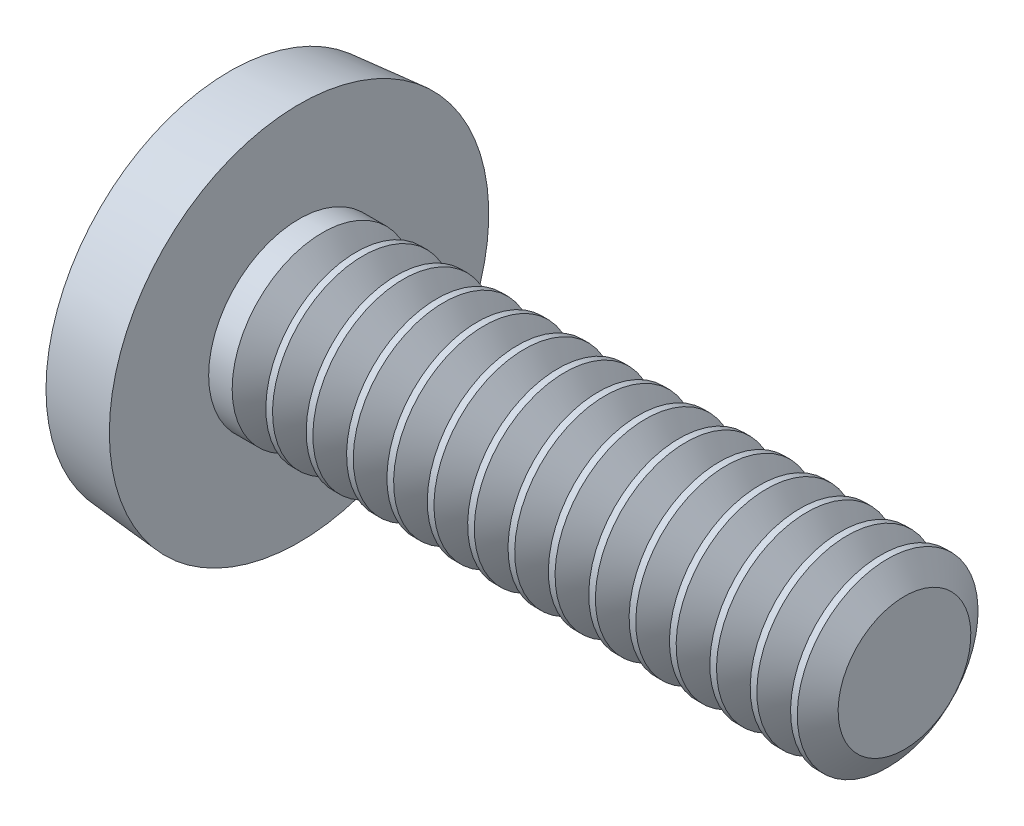
SolidWorks part; units mm, degrees
material "6061 Alloy"
ref_plane "Plane1" through (0, 0, 0) normal (0, 0, 1) x (1, 0, 0)
ref_plane "Plane2" through (0, 0, 0) normal (0, 1, 0) x (1, 0, 0)
ref_plane "Plane3" through (0, 0, 0) normal (1, 0, 0) x (0, 0, -1)
sketch "BodySke" plane through (0, 0, 0) normal (0, 0, 1) x (1, 0, 0)
  line L0 (1.7272, 1.4224) -> (1.7272, 2.9845)
  line L1 (1.7272, 2.9845) -> (0.635, 2.8889)
  line L2 (-25.4, 0) -> (127, 0) construction
  line L3 (1.7272, -2.9845) -> (0.635, -2.8889) construction
  line L4 (1.7272, 1.4224) -> (11.2522, 1.4224)
  line L5 (11.2522, 1.4224) -> (11.2522, 0)
  line L6 (11.2522, 0) -> (0, 0)
  line L7 (1.7272, -1.4224) -> (11.2522, -1.4224) construction
  line L8 (2.3622, 6.35) -> (2.3622, -3.175) construction
  line L9 (1.7272, 6.35) -> (1.7272, -3.175) construction
  arc A0 (0, 0) -> (0.635, 2.8889) centre (6.8892, 0) cw
  dimension "Head_ang" = 85
  dimension "Oval_ht" = 0.635
  dimension "Head_ht" = 1.7272
  dimension "Diameter" = 2.8448
  dimension "Length" = 9.525
  dimension "Head_dia" = 5.969
  dimension "Advance" = 0.635
  dimension "Thread_nom" = 9.525
revolve "Base-Revolve" add sketch "BodySke" angle 360 about L2
cosmetic thread "ThreadCosmetic" [suppressed] parameters "Thread_length"=8.89, "Thread_minor"=2.0879
sketch "Sketch2" plane through (0, 0, 0) normal (1, 0, 0) x (0, 0, -1)
  line L0 (2.9845, -0.4953) -> (2.9845, 0.4953)
  line L1 (2.9845, 0.4953) -> (-2.9845, 0.4953)
  line L2 (-2.9845, 0.4953) -> (-2.9845, -0.4953)
  line L3 (-2.9845, -0.4953) -> (2.9845, -0.4953)
  dimension "D1" = 5.969
  dimension "D2" = 2.9845
  dimension "D3" = 0.4953
  dimension "Slot_width" = 0.9906
extrude "Slot" [suppressed] cut sketch "Sketch2" along normal blind 1.0668
sketch "Sketch3" plane through (0, 0, 0) normal (1, 0, 0) x (0, 0, -1)
  line L0 (-0.4318, 1.9558) -> (0.4318, 1.9558)
  line L1 (0.4318, 1.9558) -> (0.4318, -1.9558)
  line L2 (0.4318, -1.9558) -> (-0.4318, -1.9558)
  line L3 (-0.4318, -1.9558) -> (-0.4318, 1.9558)
  dimension "D1" = 0.4318
  dimension "Cross_width" = 0.8636
  dimension "D2" = 1.9558
  dimension "Cross_dia" = 3.9116
ref_plane "Plane4" through (2.1844, 0, 0) normal (1, 0, 0) x (0, 0, -1)
sketch "Sketch4" plane through (2.1844, 0, 0) normal (1, 0, 0) x (0, 0, -1)
  line L0 (-0.2159, 0.2159) -> (0.2159, 0.2159)
  line L1 (0.2159, 0.2159) -> (0.2159, -0.2159)
  line L2 (0.2159, -0.2159) -> (-0.2159, -0.2159)
  line L3 (-0.2159, -0.2159) -> (-0.2159, 0.2159)
  dimension "D1" = 0.4318
  dimension "D2" = 0.2159
  dimension "D3" = 0.4318
  dimension "D4" = 0.2159
loft "Cross" cut profiles "Sketch3", "Sketch4"
pattern_circular "CirPattern1" count 2 every 90 about axis through (0, 0, 0) along (1, 0, 0) of "Cross"
sketch "ThdSchSke" plane through (0, 0, 0) normal (0, 0, 1) x (1, 0, 0)
  line L0 (2.3622, -1.0439) -> (2.0972, -1.4224)
  line L1 (2.3622, -1.0439) -> (2.6272, -1.4224)
  line L2 (2.6272, -1.4224) -> (2.6272, -1.778)
  line L3 (-3.175, 0) -> (5.1513, 0) construction
  line L5 (2.6272, -1.778) -> (2.0972, -1.778)
  line L6 (2.0972, -1.778) -> (2.0972, -1.4224)
  dimension "Thread_minor" = 2.0879
  dimension "Diameter" = 2.8448
  dimension "Start" = 2.3622
  dimension "SideAngle" = 55
  dimension "VeeAngle" = 70
  dimension "Overcut" = 3.556
revolve "ThreadSchematic" cut sketch "ThdSchSke" angle 360 about L3
pattern_linear "ThdSchPat" count 15 spacing 0.635 along (1, 0, 0) of "ThreadSchematic"
equation "\"D1@Sketch3\" = \"Cross_width@Sketch3\" / 2"
equation "\"D2@Sketch3\" = \"Cross_dia@Sketch3\" / 2"
equation "\"D1@Sketch4\" = \"Cross_width@Sketch3\"*.5"
equation "\"D2@Sketch4\" = \"D1@Sketch4\" / 2"
equation "\"D3@Sketch4\" = \"D1@Sketch4\""
equation "\"D4@Sketch4\" = \"D2@Sketch4\""
equation "\"D1@Sketch2\" = \"Head_dia@BodySke\""
equation "\"D2@Sketch2\" = \"D1@Sketch2\" / 2"
equation "\"D3@Sketch2\" = \"Slot_width@Sketch2\" / 2"
equation "\"Thread_length@ThreadCosmetic\" = ((sgn( (\"Length@BodySke\" - \"Advance@BodySke\" ) - \"Thread_nom@BodySke\" )-1)*( (\"Length@BodySke\" - \"Advance@BodySke\" ) - \"Thread_nom@BodySke\" ))/-2+ \"Thread_nom@BodySke\""
equation "\"Thread_minor@ThdSchSke\" = \"Thread_minor@ThreadCosmetic\""
equation "\"Diameter@ThdSchSke\" = \"Diameter@BodySke\""
equation "\"Overcut@ThdSchSke\" = \"Diameter@BodySke\" * 1.25"
equation "\"Start@ThdSchSke\" = \"Head_ht@BodySke\" + \"Length@BodySke\" - \"Thread_length@ThreadCosmetic\"  '---Non-countersunk---"
equation "\"Num_threads@ThdSchPat\" = int( \"Thread_length@ThreadCosmetic\" / \"Advance@BodySke\" + 0.999 )  + 1"
equation "\"Advance@ThdSchPat\" = \"Thread_length@ThreadCosmetic\" /  (\"Num_threads@ThdSchPat\" - 1) 'relax it"
